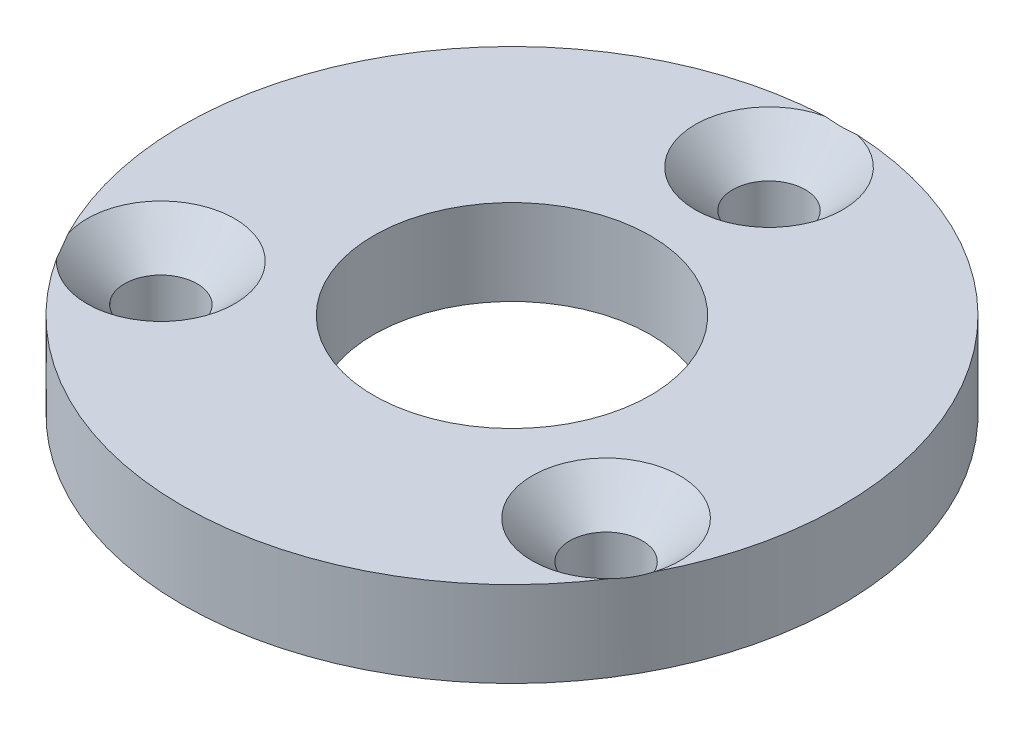
SolidWorks part; units mm, degrees
ref_plane "Alzado" through (0, 0, 0) normal (0, 0, 1) x (1, 0, 0)
ref_plane "Planta" through (0, 0, 0) normal (0, 1, 0) x (1, 0, 0)
ref_plane "Vista lateral" through (0, 0, 0) normal (1, 0, 0) x (0, 0, -1)
sketch "Sketch1" plane through (0, 0, 0) normal (0, 1, 0) x (1, 0, 0)
  circle A0 centre (0, 0) radius 25
  circle A1 centre (0, 0) radius 10.5
  dimension "D1" = 21
  dimension "D2" = 50
extrude "Boss-Extrude1" add sketch "Sketch1" along normal blind 6.5
sketch "Sketch2" plane through (0, 6.5, 0) normal (0, 1, 0) x (1, 0, 0)
  line L0 (14.2875, -14.2533) -> (19.4875, -14.2533)
  line L1 (5.2, 19.5) -> (2.6, 24.0033)
  line L2 (2.6, 24.0033) -> (-2.6, 24.0033)
  line L3 (-2.6, 24.0033) -> (-5.2, 19.5)
  line L4 (-5.2, 19.5) -> (-2.6, 14.9967)
  line L5 (-2.6, 14.9967) -> (2.6, 14.9967)
  line L6 (2.6, 14.9967) -> (5.2, 19.5)
  line L7 (19.4875, -14.2533) -> (22.0875, -9.75)
  line L8 (22.0875, -9.75) -> (19.4875, -5.2467)
  line L9 (19.4875, -5.2467) -> (14.2875, -5.2467)
  line L10 (14.2875, -5.2467) -> (11.6875, -9.75)
  line L11 (11.6875, -9.75) -> (14.2875, -14.2533)
  line L12 (-19.4875, -5.2467) -> (-22.0875, -9.75)
  line L13 (-22.0875, -9.75) -> (-19.4875, -14.2533)
  line L14 (-19.4875, -14.2533) -> (-14.2875, -14.2533)
  line L15 (-14.2875, -14.2533) -> (-11.6875, -9.75)
  line L16 (-11.6875, -9.75) -> (-14.2875, -5.2467)
  line L17 (-14.2875, -5.2467) -> (-19.4875, -5.2467)
  circle A0 centre (0, 0) radius 19.5 construction
  circle A1 centre (0, 19.5) radius 4.5033 construction
  point P25 (0, 0)
  point P32 (0, 0)
  dimension "D1" = 39
  dimension "D2" = 5.2
  dimension "D3" = 3
hole_wizard "CSK for M5 SFHCS1" positions "Sketch4" profile "Sketch5" countersink size "M5" standard "ANSI Metric" end condition through all
sketch "Sketch4" plane through (0, 6.5, 0) normal (0, 1, 0) x (1, 0, 0)
  point P0 (0, 19.5)
sketch "Sketch5" plane through (0, 6.5, -19.5) normal (1, 0, 0) x (0, 0, 1)
  line L0 (0, 0) -> (0, 6.5)
  line L1 (0, 6.5) -> (2.75, 6.5)
  line L2 (2.75, 6.5) -> (2.75, 2.85)
  line L3 (2.75, 2.85) -> (5.6, 0)
  line L5 (5.6, 0) -> (0, 0)
  line L6 (-2.75, 2.85) -> (-5.6, 0) construction
  line L11 (0, -6.35) -> (0, 107.95) construction
  dimension "Thru Hole Dia." = 5.5
  dimension "Thru Hole Depth" = 6.5
  dimension "Near C'Sink Dia." = 11.2
  dimension "Near C'Sink Angle" = 90
pattern_circular "CirPattern1" count 3 over 360 about axis through (0, 0, 0) along (0, 1, 0) of "CSK for M5 SFHCS1"
